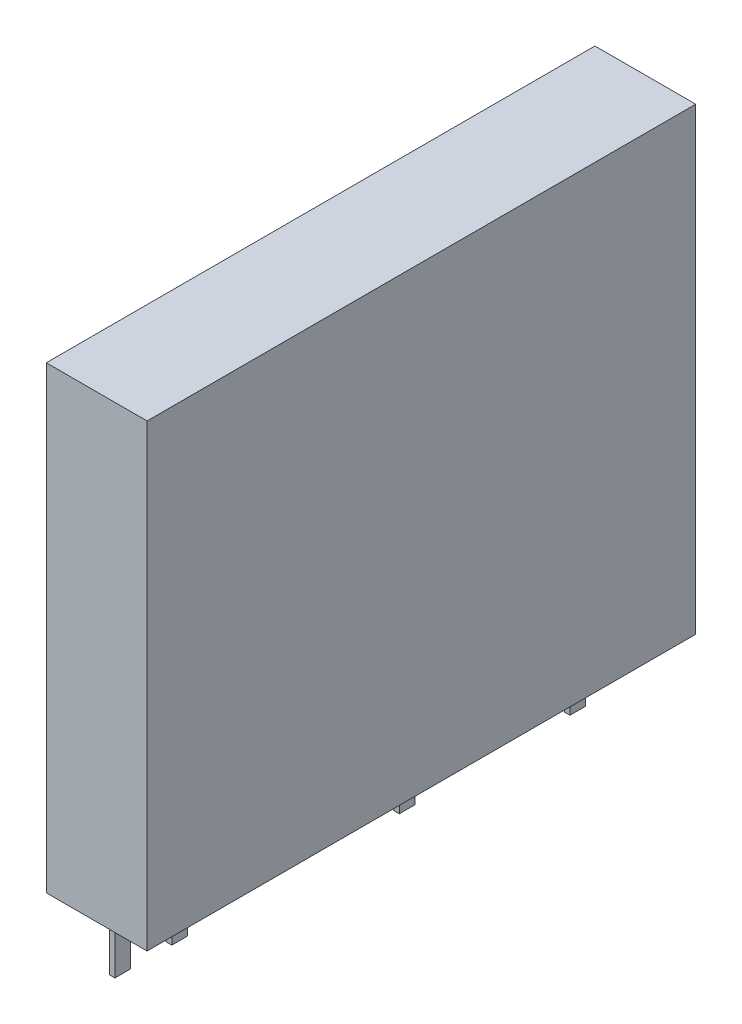
SolidWorks part; units mm, degrees
ref_plane "Спереди" through (0, 0, 0) normal (0, 0, 1) x (1, 0, 0)
ref_plane "Сверху" through (0, 0, 0) normal (0, 1, 0) x (1, 0, 0)
ref_plane "Справа" through (0, 0, 0) normal (1, 0, 0) x (0, 0, -1)
sketch "Sketch1" plane through (0, 0, 0) normal (1, 0, 0) x (0, 0, -1)
  line L1 (-12.25, -10.25) -> (12.25, -10.25)
  line L2 (-12.25, -10.25) -> (-12.25, 10.25)
  line L3 (-12.25, 10.25) -> (12.25, 10.25)
  line L4 (12.25, -10.25) -> (12.25, 10.25)
  line L5 (-12.25, -10.25) -> (12.25, 10.25) construction
  line L6 (-12.25, 10.25) -> (12.25, -10.25) construction
  point P0 (0, 0)
  dimension "D1" = 24.5
  dimension "D2" = 20.5
extrude "Boss-Extrude1" add sketch "Sketch1" along normal blind 4.5
sketch "Sketch2" plane through (0, -10.25, 0) normal (0, -1, 0) x (1, 0, 0)
  line L0 (1.2, 12.25) -> (1.2, -12.25) construction
  line L1 (4.5, 12.25) -> (0, 12.25) construction
  line L2 (4.5, -12.25) -> (0, -12.25) construction
  line L3 (1.325, 7.97) -> (1.075, 7.97)
  line L4 (1.325, 10.51) -> (1.075, 10.51)
  line L5 (1.325, 10.51) -> (1.325, 9.81)
  line L6 (1.325, 9.81) -> (1.075, 9.81)
  line L7 (1.075, 10.51) -> (1.075, 9.81)
  line L8 (1.325, 10.51) -> (1.075, 9.81) construction
  line L9 (1.325, 9.81) -> (1.075, 10.51) construction
  line L10 (1.325, 7.97) -> (1.325, 7.27)
  line L11 (1.325, 7.27) -> (1.075, 7.27)
  line L12 (1.075, 7.97) -> (1.075, 7.27)
  line L13 (1.325, 7.97) -> (1.075, 7.27) construction
  line L14 (1.325, 7.27) -> (1.075, 7.97) construction
  line L15 (1.325, -2.19) -> (1.075, -2.19)
  line L16 (1.325, -2.19) -> (1.325, -2.89)
  line L17 (1.325, -2.89) -> (1.075, -2.89)
  line L18 (1.075, -2.19) -> (1.075, -2.89)
  line L19 (1.325, -2.19) -> (1.075, -2.89) construction
  line L20 (1.325, -2.89) -> (1.075, -2.19) construction
  line L21 (1.325, -9.81) -> (1.075, -9.81)
  line L22 (1.325, -9.81) -> (1.325, -10.51)
  line L23 (1.325, -10.51) -> (1.075, -10.51)
  line L24 (1.075, -9.81) -> (1.075, -10.51)
  line L25 (1.325, -9.81) -> (1.075, -10.51) construction
  line L26 (1.325, -10.51) -> (1.075, -9.81) construction
  line L27 (0, 12.25) -> (0, -12.25) construction
  line L28 (4.5, 0) -> (0, 0) construction
  line L29 (4.5, 12.25) -> (4.5, -12.25) construction
  point P6 (1.2, 10.16)
  point P11 (1.2, 7.62)
  point P17 (1.2, -2.54)
  point P22 (1.2, -10.16)
  dimension "D1" = 1.2
  dimension "D2" = 2.54
  dimension "D3" = 7.62
  dimension "D4" = 2.54
  dimension "D5" = 10.16
extrude "Boss-Extrude2" add sketch "Sketch2" along normal blind 3.5
